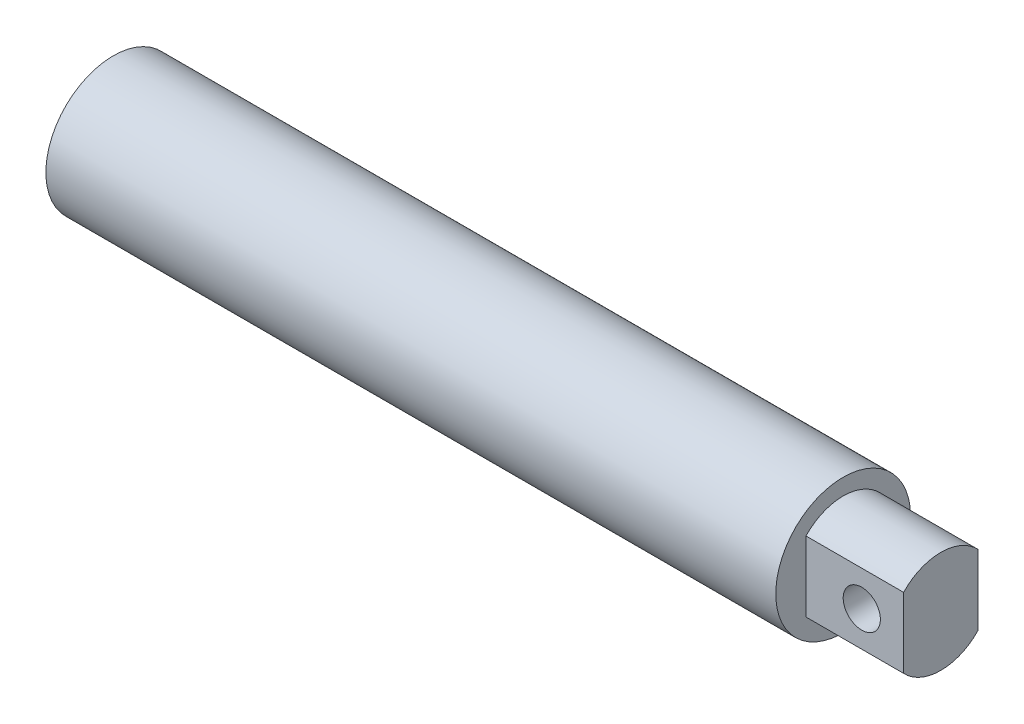
SolidWorks part; units mm, degrees
ref_plane "前视基准面" through (0, 0, 0) normal (0, 0, 1) x (1, 0, 0)
ref_plane "上视基准面" through (0, 0, 0) normal (0, 1, 0) x (1, 0, 0)
ref_plane "右视基准面" through (0, 0, 0) normal (1, 0, 0) x (0, 0, -1)
sketch "草图1" plane through (0, 0, 0) normal (1, 0, 0) x (0, 0, -1)
  circle A0 centre (0, 0) radius 14.5
  dimension "D1" = 29
extrude "凸台-拉伸1" add sketch "草图1" along normal blind 157
sketch "草图2" plane through (157, 0, 0) normal (1, 0, 0) x (0, 0, -1)
  line L0 (-8, 7.5498) -> (-8, -7.5498)
  line L2 (8, -7.5498) -> (8, 7.5498)
  arc A0 (-8, -7.5498) -> (8, -7.5498) centre (0, 0) ccw
  arc A1 (8, 7.5498) -> (-8, 7.5498) centre (0, 0) ccw
  dimension "D1" = 22
  dimension "D2" = 8
  dimension "D3" = 16
extrude "凸台-拉伸2" add sketch "草图2" along normal blind 21
sketch "草图3" plane through (0, 0, 8) normal (0, 0, 1) x (1, 0, 0)
  line L0 (157, -14.5) -> (157, 14.5) construction
  circle A0 centre (169, 0) radius 4
  dimension "D2" = 8
  dimension "D1" = 12
extrude "切除-拉伸1" cut sketch "草图3" against normal blind 21
sketch "草图4" plane through (0, 0, 0) normal (-1, 0, 0) x (0, 0, 1)
  circle A0 centre (0, 0) radius 4
  dimension "D1" = 8
extrude "切除-拉伸2" cut sketch "草图4" against normal blind 80
